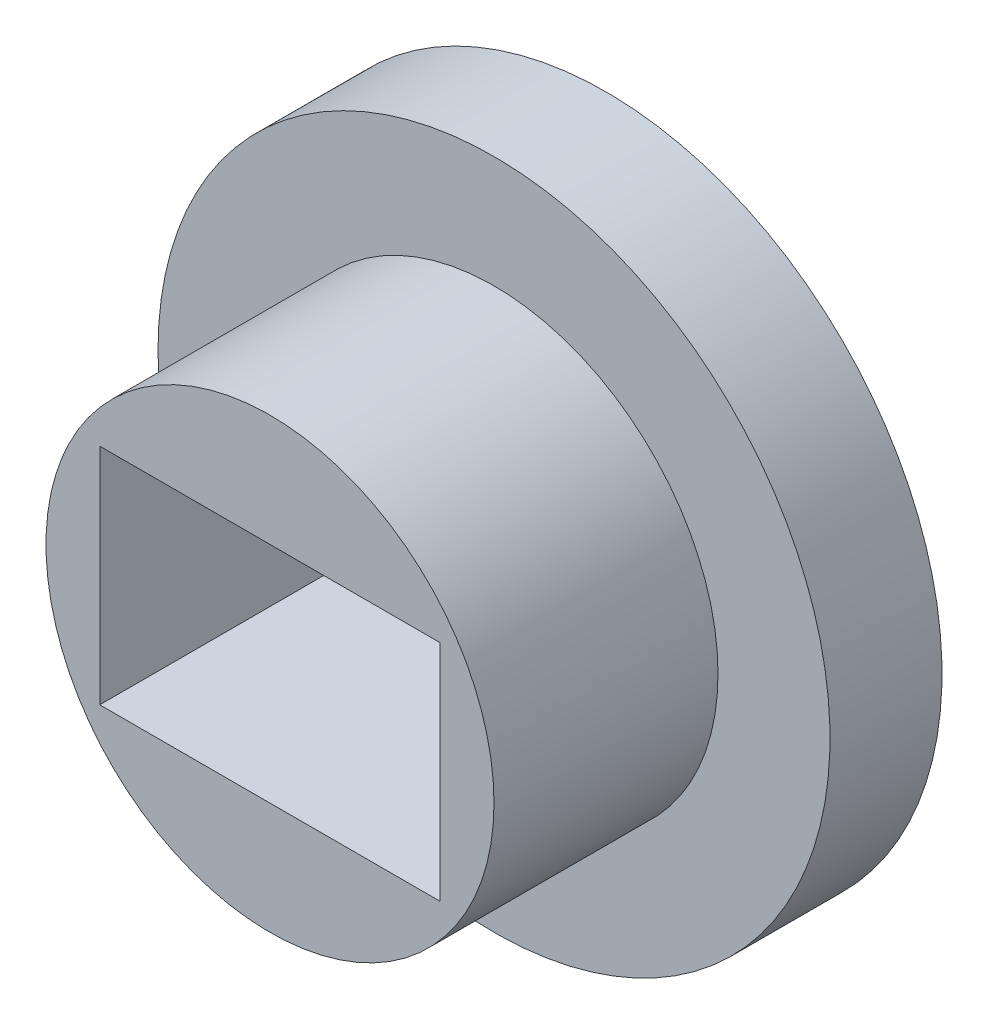
SolidWorks part; units mm, degrees
ref_plane "Front Plane" through (0, 0, 0) normal (0, 0, 1) x (1, 0, 0)
ref_plane "Top Plane" through (0, 0, 0) normal (0, 1, 0) x (1, 0, 0)
ref_plane "Right Plane" through (0, 0, 0) normal (1, 0, 0) x (0, 0, -1)
sketch "Sketch1" plane through (0, 0, 0) normal (0, 0, 1) x (1, 0, 0)
  circle A0 centre (0, 0) radius 6.35
  dimension "D1" = 12.7
extrude "Boss-Extrude1" add sketch "Sketch1" along normal blind 6.35
sketch "Sketch3" plane through (0, 0, 0) normal (0, 0, -1) x (-1, 0, 0)
  circle A0 centre (0, 0) radius 9.525
  dimension "D1" = 19.05
extrude "Boss-Extrude2" add sketch "Sketch3" along normal blind 3.175
sketch "Sketch4" plane through (0, 0, -3.175) normal (0, 0, -1) x (-1, 0, 0)
  line L1 (4.826, -3.175) -> (-4.826, -3.175)
  line L2 (4.826, -3.175) -> (4.826, 3.175)
  line L3 (4.826, 3.175) -> (-4.826, 3.175)
  line L4 (-4.826, -3.175) -> (-4.826, 3.175)
  line L5 (4.826, -3.175) -> (-4.826, 3.175) construction
  line L6 (4.826, 3.175) -> (-4.826, -3.175) construction
  point P0 (0, 0)
  dimension "D1" = 6.35
  dimension "D2" = 9.652
extrude "Cut-Extrude2" cut sketch "Sketch4" against normal through all
